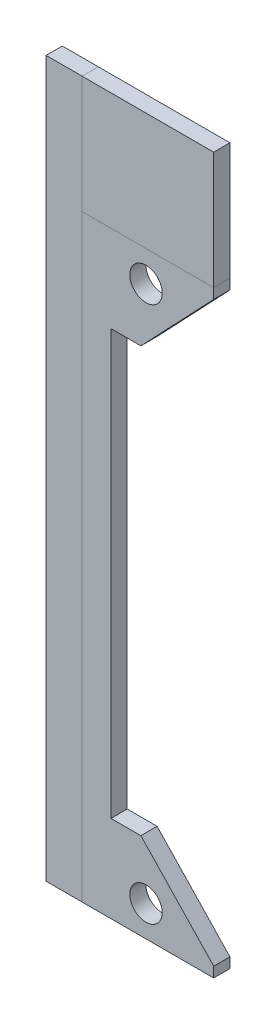
SolidWorks part; units mm, degrees
material "AISI 4340 Steel, annealed"
ref_plane "X-Y Datum" through (0, 0, 0) normal (0, 0, 1) x (1, 0, 0)
ref_plane "X-Z Datum" through (0, 0, 0) normal (0, 1, 0) x (1, 0, 0)
ref_plane "Y-Z Datum" through (0, 0, 0) normal (1, 0, 0) x (0, 0, -1)
sketch3d "3DSketch1"
  line L0 (-464.25, 116.5, 0) -> (-464.25, 118.5, 0)
  line L1 (-464.25, 118.5, 0) -> (-490, 118.5, 0)
  line L2 (-490, 118.5, 0) -> (-490, 1.5, 0)
  line L3 (-490, 1.5, 0) -> (-464.25, 1.5, 0)
  line L12 (-490, 1.5, 0) -> (0, 1.5, 0) construction
  line L13 (-464.25, 3.5, 0) -> (-464.25, 1.5, 0)
  line L14 (0, 118.5, 0) -> (-490, 118.5, 0) construction
  line L15 (-464.25, 3.5, 0) -> (-478.5, 18.5, 0)
  line L16 (-478.5, 18.5, 0) -> (-484.35, 18.5, 0)
  line L17 (-484.35, 18.5, 0) -> (-484.35, 101.5, 0)
  line L18 (-484.35, 101.5, 0) -> (-478.5, 101.5, 0)
  line L19 (-478.5, 101.5, 0) -> (-464.25, 116.5, 0)
  line L20 (-477.5, 7.5, -1) -> (-477.5, 7.5, 0) construction
  line L21 (-477.5, 112.5, -1) -> (-477.5, 112.5, 0) construction
  line L23 (-490, 118.5, 0) -> (-464.25, 118.5, 0)
  line L24 (-490, 118.5, 0) -> (-490, 141.4598, 0)
  line L25 (-490, 141.4598, 0) -> (-464.25, 141.4598, 0)
  line L26 (-464.25, 118.5, 0) -> (-464.25, 141.4598, 0)
  line L27 (-490, 1.5, 0) -> (-497.05, 1.5, 0)
  line L28 (-490, 1.5, 0) -> (-490, 141.4598, 0)
  line L29 (-490, 141.4598, 0) -> (-497.05, 141.4598, 0)
  line L30 (-497.05, 1.5, 0) -> (-497.05, 141.4598, 0)
  circle A0 centre (-477.5, 7.5, 0) radius 3.175
  circle A1 centre (-477.5, 112.5, 0) radius 3.175
  point P24 (-477.5, 7.5, 3.175)
  point P29 (-477.5, 112.5, 3.175)
  dimension "D1" = 6.35
  dimension "D2" = 6.35
  dimension "D3" = 12.7
extrude "Boss-Extrude1" add sketch "3DSketch1" along a picked direction on the side against the normal blind 3.175 contours L0 L1 L2 L3 L13 L15 L16 L17 L18 L19 | L24 L23 L26 L25 | A1 | A0 | L30 L29 L28 L27
